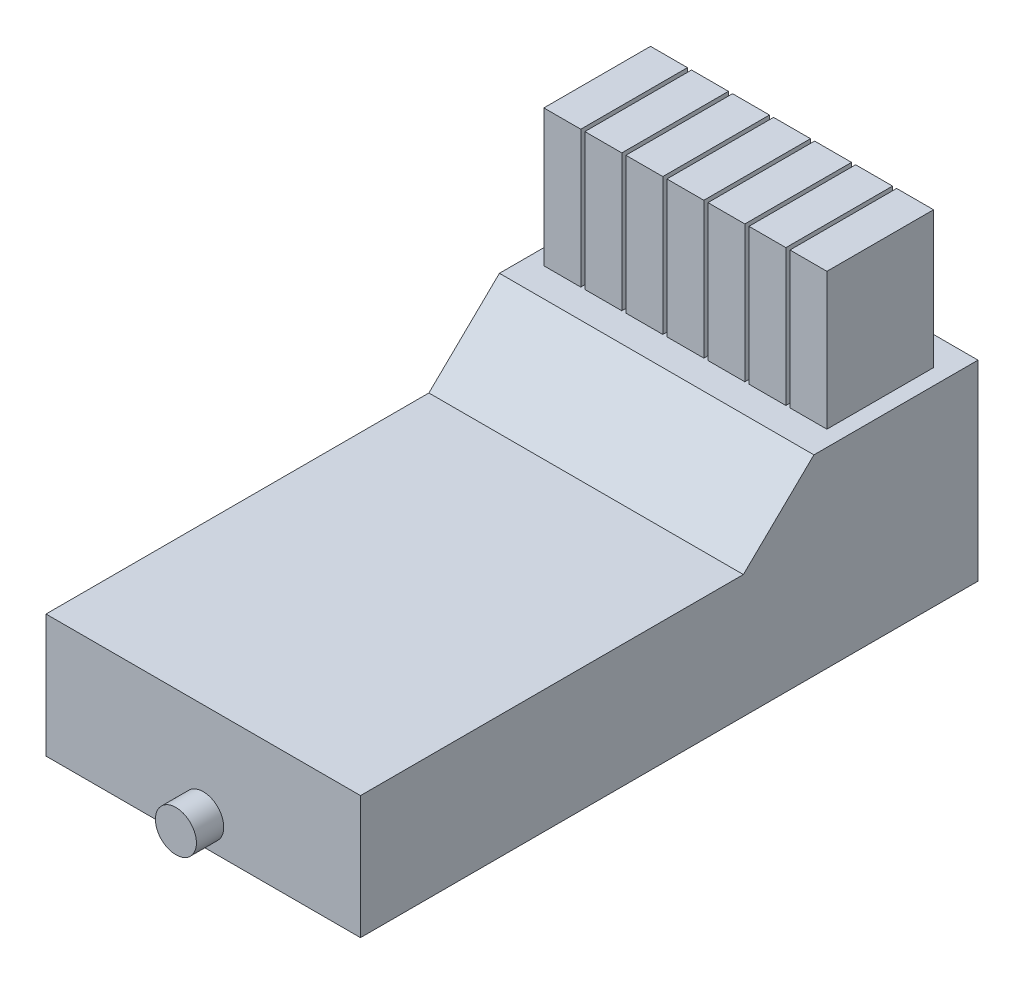
SolidWorks part; units mm, degrees
ref_plane "Front Plane" through (0, 0, 0) normal (0, 0, 1) x (1, 0, 0)
ref_plane "Top Plane" through (0, 0, 0) normal (0, 1, 0) x (1, 0, 0)
ref_plane "Right Plane" through (0, 0, 0) normal (1, 0, 0) x (0, 0, -1)
sketch "Sketch1" plane through (0, 0, 0) normal (1, 0, 0) x (0, 0, -1)
  line L0 (0, 0) -> (0, 9)
  line L1 (0, 9) -> (28, 9)
  line L2 (28, 9) -> (33.16, 14)
  line L3 (33.16, 14) -> (45.16, 14)
  line L4 (45.16, 14) -> (45.16, 0)
  line L5 (45.16, 0) -> (0, 0)
  dimension "D1" = 45.16
  dimension "D2" = 14
  dimension "D3" = 9
  dimension "D4" = 28
  dimension "D5" = 12
extrude "Boss-Extrude1" add sketch "Sketch1" along normal blind 23
sketch "Sketch2" plane through (0, 0, 0) normal (0, 0, 1) x (1, 0, 0)
  line L0 (11.5, 0) -> (11.5, 9) construction
  line L1 (23, 0) -> (0, 0) construction
  line L2 (23, 9) -> (0, 9) construction
  circle A0 centre (11.5, 2) radius 1.5
  dimension "D1" = 3
  dimension "D2" = 2
extrude "Boss-Extrude2" add sketch "Sketch2" along normal blind 2
sketch "Sketch3" plane through (0, 14, 0) normal (0, 1, 0) x (1, 0, 0)
  line L0 (11.5, 45.16) -> (11.5, 33.16) construction
  line L1 (23, 45.16) -> (0, 45.16) construction
  line L2 (23, 33.16) -> (0, 33.16) construction
  line L3 (11.5, 33.16) -> (11.5, 45.16) construction
  line L4 (13.15, 43.06) -> (13.15, 35.26)
  line L5 (10.15, 43.06) -> (12.85, 43.06)
  line L6 (10.15, 43.06) -> (10.15, 35.26)
  line L7 (10.15, 35.26) -> (12.85, 35.26)
  line L8 (12.85, 43.06) -> (12.85, 35.26)
  line L9 (10.15, 43.06) -> (12.85, 35.26) construction
  line L10 (10.15, 35.26) -> (12.85, 43.06) construction
  line L11 (13.15, 43.06) -> (15.85, 43.06)
  line L12 (15.85, 43.06) -> (15.85, 35.26)
  line L13 (13.15, 35.26) -> (15.85, 35.26)
  line L14 (16.15, 43.06) -> (16.15, 35.26)
  line L15 (16.15, 43.06) -> (18.85, 43.06)
  line L16 (18.85, 43.06) -> (18.85, 35.26)
  line L17 (16.15, 35.26) -> (18.85, 35.26)
  line L18 (19.15, 43.06) -> (19.15, 35.26)
  line L19 (19.15, 43.06) -> (21.85, 43.06)
  line L20 (21.85, 43.06) -> (21.85, 35.26)
  line L21 (19.15, 35.26) -> (21.85, 35.26)
  line L22 (7.15, 43.06) -> (7.15, 35.26)
  line L23 (7.15, 43.06) -> (9.85, 43.06)
  line L24 (9.85, 43.06) -> (9.85, 35.26)
  line L25 (7.15, 35.26) -> (9.85, 35.26)
  line L26 (4.15, 43.06) -> (4.15, 35.26)
  line L27 (4.15, 43.06) -> (6.85, 43.06)
  line L28 (6.85, 43.06) -> (6.85, 35.26)
  line L29 (4.15, 35.26) -> (6.85, 35.26)
  line L30 (1.15, 43.06) -> (1.15, 35.26)
  line L31 (1.15, 43.06) -> (3.85, 43.06)
  line L32 (3.85, 43.06) -> (3.85, 35.26)
  line L33 (1.15, 35.26) -> (3.85, 35.26)
  point P6 (11.5, 39.16)
  dimension "D1" = 7.8
  dimension "D2" = 2.7
  dimension "D3" = 4
  dimension "D4" = 4
extrude "Boss-Extrude3" add sketch "Sketch3" along normal blind 10
